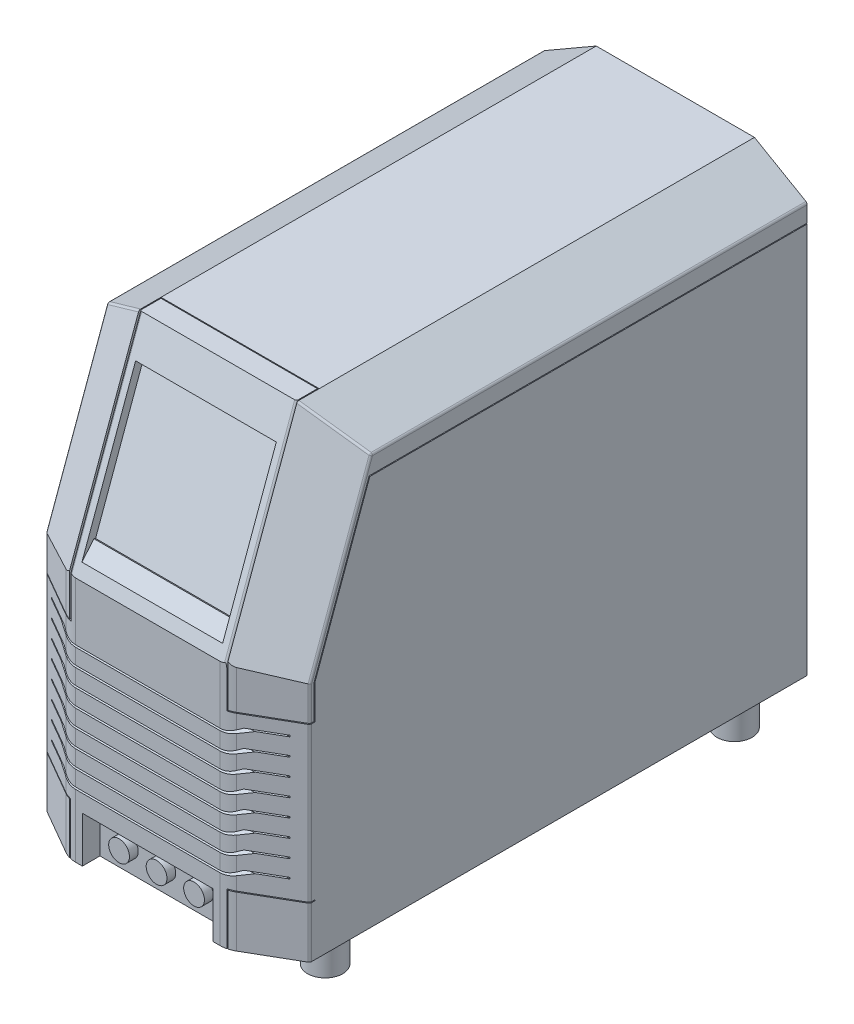
SolidWorks part; units mm, degrees
ref_plane "前视基准面" through (0, 0, 0) normal (0, 0, 1) x (1, 0, 0)
ref_plane "上视基准面" through (0, 0, 0) normal (0, 1, 0) x (1, 0, 0)
ref_plane "右视基准面" through (0, 0, 0) normal (1, 0, 0) x (0, 0, -1)
sketch "草图1" plane through (0, 0, 0) normal (0, 1, 0) x (1, 0, 0)
  line L1 (-150, -300) -> (150, -300)
  line L2 (-150, -300) -> (-150, 300)
  line L3 (-150, 300) -> (150, 300)
  line L4 (150, -300) -> (150, 300)
  line L5 (-150, -300) -> (150, 300) construction
  line L6 (-150, 300) -> (150, -300) construction
  point P0 (0, 0)
  dimension "D1" = 300
  dimension "D2" = 600
extrude "凸台-拉伸1" add sketch "草图1" along normal blind 500
chamfer "倒角1" distance 220 angle 20 1 edges at (0, 500, 300)
chamfer "倒角2" distance 60 angle 30 2 edges at (150, 500, -40.0367) (150, 390, 259.9633)
chamfer "倒角3" distance 60 angle 30 2 edges at (-150, 500, -40.0367) (-150, 390, 259.9633)
sketch "草图3" plane through (0, 0, 300) normal (0, 0, 1) x (1, 0, 0)
  line L0 (0, 500) -> (0, 261.5759) construction
  line L1 (90, 280) -> (89, 280)
  line L2 (90, 280) -> (90, 507.6744)
  line L3 (90, 507.6744) -> (89, 507.6744)
  line L4 (89, 280) -> (89, 507.6744)
  line L5 (-90, 500) -> (90, 500) construction
  line L6 (-89, 280) -> (-89, 507.6744)
  line L7 (-90, 507.6744) -> (-89, 507.6744)
  line L8 (-90, 280) -> (-90, 507.6744)
  line L9 (-90, 280) -> (-89, 280)
  dimension "D1" = 1
extrude "切除-拉伸1" cut sketch "草图3" against normal blind 105
sketch "草图4" plane through (0, 500, 0) normal (0, 1, 0) x (1, 0, 0)
  line L0 (90, -195) -> (90, -300) construction
  line L1 (-90, -195) -> (90, -195)
  line L2 (-90, -195) -> (-90, -196)
  line L3 (-90, -196) -> (90, -196)
  line L4 (90, -195) -> (90, -196)
  dimension "D1" = 1
extrude "切除-拉伸2" cut sketch "草图4" against normal blind 22
sketch "草图6" plane through (0, 0, 300) normal (0, 0, 1) x (1, 0, 0)
  line L0 (150, 273.8919) -> (150, 0) construction
  line L1 (150, 58.0888) -> (90, 58.0888)
  line L2 (150, 58.0888) -> (150, 59.0888)
  line L3 (150, 59.0888) -> (90, 59.0888)
  line L4 (90, 58.0888) -> (90, 59.0888)
  line L5 (90, 0) -> (90, 280) construction
  line L6 (0, 0) -> (0, 258.275) construction
  line L7 (150, 234.1862) -> (90, 234.1862)
  line L8 (150, 234.1862) -> (150, 235.1862)
  line L9 (150, 235.1862) -> (90, 235.1862)
  line L10 (90, 234.1862) -> (90, 235.1862)
  line L11 (-90, 234.1862) -> (-90, 235.1862)
  line L12 (-150, 235.1862) -> (-90, 235.1862)
  line L13 (-150, 234.1862) -> (-150, 235.1862)
  line L14 (-150, 234.1862) -> (-90, 234.1862)
  line L15 (-90, 58.0888) -> (-90, 59.0888)
  line L16 (-150, 59.0888) -> (-90, 59.0888)
  line L17 (-150, 58.0888) -> (-150, 59.0888)
  line L18 (-150, 58.0888) -> (-90, 58.0888)
  dimension "D1" = 1
  dimension "D2" = 1
extrude "切除-拉伸3" cut sketch "草图6" against normal blind 40
sketch "草图8" plane through (150, 0, 0) normal (1, 0, 0) x (0, 0, -1)
  line L4 (-197.4868, 444.6975) -> (300, 444.6975)
  line L5 (300, 465.359) -> (300, 0) construction
  line L6 (-190.6339, 463.5258) -> (-259.999, 272.9467)
  line L7 (-259.999, 272.9467) -> (-259.999, 235.1862)
  line L8 (-197.4868, 444.6975) -> (-259.999, 272.9467)
  line L9 (-259.999, 272.9467) -> (-259.999, 235.1862)
  line L10 (-198.187, 445.6975) -> (300, 445.6975)
  line L11 (-198.187, 445.6975) -> (-260.999, 273.1231)
  line L12 (-260.999, 273.1231) -> (-260.999, 235.1862)
  line L13 (300, 445.6975) -> (300, 444.6975)
  line L14 (-259.999, 235.1862) -> (-260.999, 235.1862)
  dimension "D1" = 5.36
  dimension "D2" = 1
extrude "切除-拉伸8" cut sketch "草图8" against normal blind 36
mirror "镜向1" about plane through (0, 0, 0) normal (1, 0, 0) of "切除-拉伸8"
fillet "圆角1" radius 3 12 edges at (-150, 29.0444, 265.359) (-150, 146.6375, 265.359) (-150, 254.539, 265.359) (-120, 482.6795, 207.7986) (-150, 369.6254, 230.5148) (-150, 465.359, -52.1647) (120, 482.6795, 207.7986) (150, 29.0444, 265.359) (150, 146.6375, 265.359) (150, 254.539, 265.359) (150, 369.6254, 230.5148) (150, 465.359, -52.1647)
sketch "草图9" plane through (0, 0, 0) normal (1, 0, 0) x (0, 0, -1)
  line L0 (-233.8154, 461.8407) -> (-226.9957, 459.3585)
  line L1 (-300, 280) -> (-220.5487, 498.2905) construction
  line L2 (-226.9957, 459.3585) -> (-281.242, 310.318)
  line L3 (-281.242, 310.318) -> (-294.8813, 294.0635)
  line L4 (-233.8154, 461.8407) -> (-294.8813, 294.0635)
extrude "切除-拉伸9" cut sketch "草图9" against normal mid plane 160
sketch "草图10" plane through (0, 126.6897, 348.0772) normal (0, 0.342, 0.9397) x (1, 0, 0)
  line L4 (80, 195.4131) -> (80, 354.0187)
  line L5 (80, 354.0187) -> (-80, 354.0187)
  line L6 (-80, 354.0187) -> (-80, 195.4131)
  line L7 (-80, 195.4131) -> (80, 195.4131)
  line L8 (80, 195.4131) -> (80, 354.0187)
  line L9 (80, 354.0187) -> (-80, 354.0187)
  line L10 (-80, 354.0187) -> (-80, 195.4131)
  line L11 (-80, 195.4131) -> (80, 195.4131)
  dimension "D1" = 0
extrude "切除-拉伸10" cut sketch "草图10" against normal blind 2
sketch "草图11" plane through (0, 0, 0) normal (0, -1, 0) x (1, 0, 0)
  line L0 (0, 300) -> (0, 229.904) construction
  line L4 (96.9615, 295.9808) -> (92.4804, 305.5043)
  line L6 (92.4804, 305.5043) -> (81.9615, 300)
  line L7 (-90, 300) -> (90, 300) construction
  line L8 (-92.4804, 305.5043) -> (-81.9615, 300)
  line L9 (-96.9615, 295.9808) -> (-92.4804, 305.5043)
  arc A0 (96.9615, 295.9808) -> (81.9615, 300) centre (81.9615, 270) ccw
  arc A1 (-96.9615, 295.9808) -> (-81.9615, 300) centre (-81.9615, 270) cw
  point P11 (90, 300)
  point P16 (-90, 300)
  dimension "D1" = 30
extrude "切除-拉伸11" cut sketch "草图11" against normal blind 375
sketch "草图14" plane through (0, 0, 300) normal (0, 0, 1) x (1, 0, 0)
  line L2 (-90, 234.1862) -> (-89, 234.1862)
  line L3 (-90, 234.1862) -> (-90, 280)
  line L4 (-90, 280) -> (-89, 280)
  line L5 (-89, 234.1862) -> (-89, 280)
  line L6 (90, 234.1862) -> (89, 234.1862)
  line L7 (90, 234.1862) -> (90, 280)
  line L8 (90, 280) -> (89, 280)
  line L9 (89, 234.1862) -> (89, 280)
extrude "切除-拉伸14" cut sketch "草图14" against normal blind 131
fillet "圆角2" radius 2 3 edges at (-89, 391.1503, 259.5446) (89, 391.1503, 259.5446) (-89, 258.2434, 299.1626)
sketch "草图12" plane through (0, 0, 300) normal (0, 0, 1) x (1, 0, 0)
  line L1 (-74.4104, -52.1139) -> (74.4104, -52.1139)
  line L2 (-74.4104, -52.1139) -> (-74.4104, 52.1139)
  line L3 (-74.4104, 52.1139) -> (74.4104, 52.1139)
  line L4 (74.4104, -52.1139) -> (74.4104, 52.1139)
  line L5 (-74.4104, -52.1139) -> (74.4104, 52.1139) construction
  line L6 (-74.4104, 52.1139) -> (74.4104, -52.1139) construction
  point P0 (0, 0)
extrude "切除-拉伸12" cut sketch "草图12" against normal blind 20
sketch "草图13" plane through (0, 0, 0) normal (1, 0, 0) x (0, 0, -1)
  line L0 (-311.5933, 206.9864) -> (-289.4556, 220.6217)
  line L1 (-311.5933, 206.9864) -> (-310.5444, 205.2835)
  line L2 (-289.4556, 220.6217) -> (-288.4067, 218.9188)
  line L3 (-310.5444, 205.2835) -> (-288.4067, 218.9188)
  line L4 (-311.5933, 206.9864) -> (-288.4067, 218.9188) construction
  line L5 (-289.4556, 220.6217) -> (-310.5444, 205.2835) construction
  line L6 (-300, 280) -> (-300, 0) construction
  line L7 (-289.4556, 200.6217) -> (-288.4067, 198.9188)
  line L8 (-311.5933, 186.9864) -> (-289.4556, 200.6217)
  line L9 (-311.5933, 186.9864) -> (-310.5444, 185.2835)
  line L10 (-310.5444, 185.2835) -> (-288.4067, 198.9188)
  line L11 (-289.4556, 180.6217) -> (-288.4067, 178.9188)
  line L12 (-311.5933, 166.9864) -> (-289.4556, 180.6217)
  line L13 (-311.5933, 166.9864) -> (-310.5444, 165.2835)
  line L14 (-310.5444, 165.2835) -> (-288.4067, 178.9188)
  line L15 (-289.4556, 160.6217) -> (-288.4067, 158.9188)
  line L16 (-311.5933, 146.9864) -> (-289.4556, 160.6217)
  line L17 (-311.5933, 146.9864) -> (-310.5444, 145.2835)
  line L18 (-310.5444, 145.2835) -> (-288.4067, 158.9188)
  line L19 (-289.4556, 140.6217) -> (-288.4067, 138.9188)
  line L20 (-311.5933, 126.9864) -> (-289.4556, 140.6217)
  line L21 (-311.5933, 126.9864) -> (-310.5444, 125.2835)
  line L22 (-310.5444, 125.2835) -> (-288.4067, 138.9188)
  line L23 (-289.4556, 120.6217) -> (-288.4067, 118.9188)
  line L24 (-311.5933, 106.9864) -> (-289.4556, 120.6217)
  line L25 (-311.5933, 106.9864) -> (-310.5444, 105.2835)
  line L26 (-310.5444, 105.2835) -> (-288.4067, 118.9188)
  line L27 (-289.4556, 100.6217) -> (-288.4067, 98.9188)
  line L28 (-311.5933, 86.9864) -> (-289.4556, 100.6217)
  line L29 (-311.5933, 86.9864) -> (-310.5444, 85.2835)
  line L30 (-310.5444, 85.2835) -> (-288.4067, 98.9188)
  line L31 (-289.4556, 80.6217) -> (-288.4067, 78.9188)
  line L32 (-311.5933, 66.9864) -> (-289.4556, 80.6217)
  line L33 (-311.5933, 66.9864) -> (-310.5444, 65.2835)
  line L34 (-310.5444, 65.2835) -> (-288.4067, 78.9188)
  point P1 (-300, 212.9526)
  dimension "D2" = 26
  dimension "D3" = 2
  dimension "D1" = 8
extrude "切除-拉伸13" cut sketch "草图13" against normal blind 131 and the other way blind 129
sketch "草图15" plane through (0, 0, 300) normal (0, 0, 1) x (1, 0, 0)
  line L0 (-96.9615, 59.0888) -> (-90, 59.0888) construction
  line L1 (90, 59.0888) -> (89, 59.0888)
  line L2 (90, 59.0888) -> (90, -9.6596)
  line L3 (90, -9.6596) -> (89, -9.6596)
  line L4 (89, 59.0888) -> (89, -9.6596)
  line L5 (-90, 59.0888) -> (-89, 59.0888)
  line L6 (-90, 59.0888) -> (-90, -9.6596)
  line L7 (-90, -9.6596) -> (-89, -9.6596)
  line L8 (-89, 59.0888) -> (-89, -9.6596)
  line L9 (-90, 59.0888) -> (-150, 59.0888) construction
  dimension "D1" = 1
  dimension "D2" = 1
extrude "切除-拉伸15" cut sketch "草图15" against normal blind 131
ref_plane "基准面2" through (110.0802, 118.9188, 288.4067) normal (0.6724, -0.6303, -0.3882) x (-0.3305, 0.2136, -0.9193)
sketch "草图17" plane through (0, 0, 0) normal (1, 0, 0) x (0, 0, -1)
  line L0 (-292.9188, 199.083) -> (-292.9188, 200.7009)
  line L1 (-273.6967, 219.083) -> (-292.9188, 219.083)
  line L2 (-273.6967, 219.083) -> (-273.6967, 220.7009)
  line L3 (-273.6967, 220.7009) -> (-292.9188, 220.7009)
  line L4 (-292.9188, 219.083) -> (-292.9188, 220.7009)
  line L5 (-273.6967, 200.7009) -> (-292.9188, 200.7009)
  line L6 (-273.6967, 199.083) -> (-292.9188, 199.083)
  line L7 (-273.6967, 199.083) -> (-273.6967, 200.7009)
  line L8 (-292.9188, 179.083) -> (-292.9188, 180.7009)
  line L9 (-273.6967, 180.7009) -> (-292.9188, 180.7009)
  line L10 (-273.6967, 179.083) -> (-292.9188, 179.083)
  line L11 (-273.6967, 179.083) -> (-273.6967, 180.7009)
  line L12 (-292.9188, 159.083) -> (-292.9188, 160.7009)
  line L13 (-273.6967, 160.7009) -> (-292.9188, 160.7009)
  line L14 (-273.6967, 159.083) -> (-292.9188, 159.083)
  line L15 (-273.6967, 159.083) -> (-273.6967, 160.7009)
  line L16 (-292.9188, 139.083) -> (-292.9188, 140.7009)
  line L17 (-273.6967, 140.7009) -> (-292.9188, 140.7009)
  line L18 (-273.6967, 139.083) -> (-292.9188, 139.083)
  line L19 (-273.6967, 139.083) -> (-273.6967, 140.7009)
  line L20 (-292.9188, 119.083) -> (-292.9188, 120.7009)
  line L21 (-273.6967, 120.7009) -> (-292.9188, 120.7009)
  line L22 (-273.6967, 119.083) -> (-292.9188, 119.083)
  line L23 (-273.6967, 119.083) -> (-273.6967, 120.7009)
  line L24 (-292.9188, 99.083) -> (-292.9188, 100.7009)
  line L25 (-273.6967, 100.7009) -> (-292.9188, 100.7009)
  line L26 (-273.6967, 99.083) -> (-292.9188, 99.083)
  line L27 (-273.6967, 99.083) -> (-273.6967, 100.7009)
  line L28 (-292.9188, 79.083) -> (-292.9188, 80.7009)
  line L29 (-273.6967, 80.7009) -> (-292.9188, 80.7009)
  line L30 (-273.6967, 79.083) -> (-292.9188, 79.083)
  line L31 (-273.6967, 79.083) -> (-273.6967, 80.7009)
  dimension "D1" = 8
extrude "切除-拉伸16" cut sketch "草图17" against normal mid plane 501
sketch "草图18" plane through (0, 0, 0) normal (1, 0, 0) x (0, 0, -1)
  line L0 (-292.9188, 220.7009) -> (-300, 214.1271)
  line L1 (-300, 214.1271) -> (-288.117, 220.7009)
  line L2 (-273.6967, 220.7009) -> (-292.9188, 220.7009) construction
  line L3 (-288.117, 220.7009) -> (-292.9188, 220.7009)
  line L4 (-292.9188, 200.7009) -> (-300, 194.1271)
  line L5 (-300, 194.1271) -> (-288.117, 200.7009)
  line L6 (-288.117, 200.7009) -> (-292.9188, 200.7009)
  line L7 (-292.9188, 180.7009) -> (-300, 174.1271)
  line L8 (-300, 174.1271) -> (-288.117, 180.7009)
  line L9 (-288.117, 180.7009) -> (-292.9188, 180.7009)
  line L10 (-292.9188, 160.7009) -> (-300, 154.1271)
  line L11 (-300, 154.1271) -> (-288.117, 160.7009)
  line L12 (-288.117, 160.7009) -> (-292.9188, 160.7009)
  line L13 (-292.9188, 140.7009) -> (-300, 134.1271)
  line L14 (-300, 134.1271) -> (-288.117, 140.7009)
  line L15 (-288.117, 140.7009) -> (-292.9188, 140.7009)
  line L16 (-292.9188, 120.7009) -> (-300, 114.1271)
  line L17 (-300, 114.1271) -> (-288.117, 120.7009)
  line L18 (-288.117, 120.7009) -> (-292.9188, 120.7009)
  line L19 (-292.9188, 100.7009) -> (-300, 94.1271)
  line L20 (-300, 94.1271) -> (-288.117, 100.7009)
  line L21 (-288.117, 100.7009) -> (-292.9188, 100.7009)
  line L22 (-292.9188, 80.7009) -> (-300, 74.1271)
  line L23 (-300, 74.1271) -> (-288.117, 80.7009)
  line L24 (-288.117, 80.7009) -> (-292.9188, 80.7009)
  dimension "D1" = 8
extrude "切除-拉伸17" cut sketch "草图18" against normal mid plane 501
sketch "草图19" plane through (0, 0, 280) normal (0, 0, 1) x (1, 0, 0)
  line L0 (-74.4104, 26.0569) -> (74.4104, 26.0569) construction
  line L1 (-74.4104, 52.1139) -> (-74.4104, 0) construction
  line L2 (74.4104, 0) -> (74.4104, 52.1139) construction
  line L3 (0, 0) -> (0, 48.4761) construction
  circle A0 centre (0, 26.0569) radius 11.8158
  circle A1 centre (-42.6403, 26.0569) radius 11.8158
  circle A2 centre (42.6403, 26.0569) radius 11.8158
extrude "凸台-拉伸2" add sketch "草图19" along normal blind 10
sketch "草图20" plane through (0, 0, 0) normal (0, -1, 0) x (1, 0, 0)
  line L0 (0, 217.9672) -> (0, -247.6013) construction
  line L1 (-119.7065, 217.9672) -> (119.7065, 217.9672) construction
  line L2 (-119.7065, 217.9672) -> (-119.7065, -247.6013) construction
  line L3 (-119.7065, -247.6013) -> (119.7065, -247.6013) construction
  line L4 (119.7065, 217.9672) -> (119.7065, -247.6013) construction
  circle A0 centre (-119.7065, 217.9672) radius 20
  circle A1 centre (119.7065, 217.9672) radius 20
  circle A2 centre (119.7065, -247.6013) radius 20
  circle A3 centre (-119.7065, -247.6013) radius 20
  dimension "D1" = 40
extrude "凸台-拉伸3" add sketch "草图20" along normal blind 40
